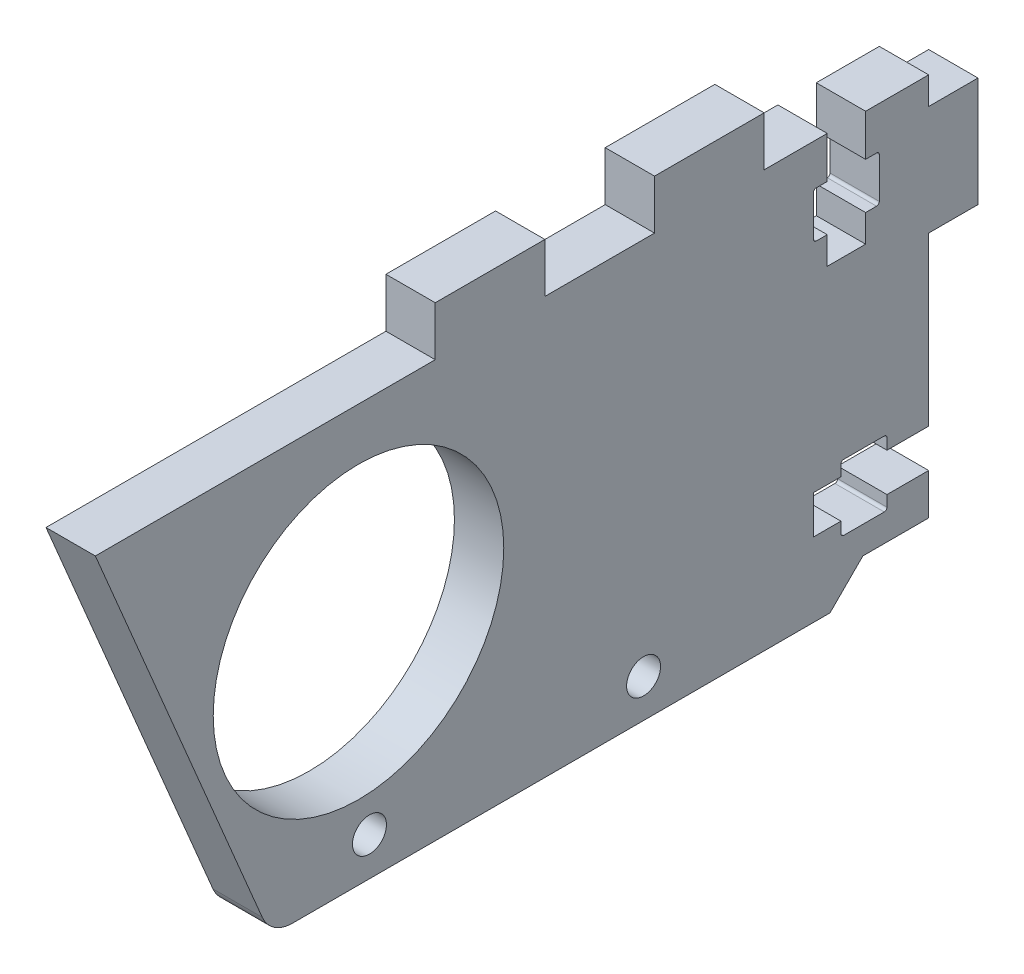
SolidWorks part; units mm, degrees
ref_plane "Front Plane" through (0, 0, 0) normal (0, 0, 1) x (1, 0, 0)
ref_plane "Top Plane" through (0, 0, 0) normal (0, 1, 0) x (1, 0, 0)
ref_plane "Right Plane" through (0, 0, 0) normal (1, 0, 0) x (0, 0, -1)
sketch "Sketch1" plane through (0, 0, 0) normal (1, 0, 0) x (0, 0, -1)
  line L0 (0, 0) -> (0, -35)
  line L1 (0, -35) -> (-76, 0)
  line L2 (-76, 0) -> (0, 0)
  dimension "D1" = 35
  dimension "D2" = 76
extrude "Boss-Extrude1" add sketch "Sketch1" along normal blind 4.5
sketch "Sketch2" plane through (4.5, 0, 0) normal (1, 0, 0) x (0, 0, -1)
  line L0 (0, -35) -> (0, 0) construction
  line L1 (-4.5, -2.5) -> (4.5, -2.5)
  line L2 (-4.5, -2.5) -> (-4.5, -12.5)
  line L3 (-4.5, -12.5) -> (4.5, -12.5)
  line L4 (4.5, -2.5) -> (4.5, -12.5)
  line L5 (-4.5, -2.5) -> (4.5, -12.5) construction
  line L6 (-4.5, -12.5) -> (4.5, -2.5) construction
  line L7 (0, 0) -> (-76, 0) construction
  point P0 (0, -7.5)
  dimension "D1" = 10
  dimension "D2" = 7.5
  dimension "D3" = 4.5
extrude "Boss-Extrude2" add sketch "Sketch2" against normal through all
sketch "Sketch3" plane through (4.5, 0, 0) normal (1, 0, 0) x (0, 0, -1)
  line L0 (0, -35) -> (-40, -35)
  line L1 (0, -25) -> (-76, 0)
  line L4 (0, -35) -> (0, -12.5) construction
  line L5 (0, -25) -> (0, -35)
  line L6 (-76, 0) -> (-40, -35)
  dimension "D1" = 40
  dimension "D2" = 10
extrude "Boss-Extrude3" add sketch "Sketch3" against normal through all
sketch "Sketch4" plane through (4.5, 0, 0) normal (1, 0, 0) x (0, 0, -1)
  line L0 (0, -29.5) -> (-10.5, -29.5) construction
  line L1 (0, -35) -> (0, -12.5) construction
  line L2 (0, -27.75) -> (-10.5, -27.75) construction
  line L3 (-10.5, -27.75) -> (-10.5, -31.25) construction
  line L4 (0, -31.25) -> (0, -27.75)
  line L5 (0, -27.75) -> (-3.8, -27.75)
  line L6 (-3.8, -27.75) -> (-3.8, -26.75)
  line L7 (-4.05, -26.5) -> (-7.75, -26.5)
  line L8 (-8, -26.75) -> (-8, -27.75)
  line L9 (-8, -27.75) -> (-10.5, -27.75)
  line L10 (-10.5, -27.75) -> (-10.5, -31.25)
  line L12 (0, -31.25) -> (-10.5, -31.25) construction
  line L13 (-8, -31.25) -> (-10.5, -31.25)
  line L14 (-8, -32.25) -> (-8, -31.25)
  line L15 (-4.05, -32.5) -> (-7.75, -32.5)
  line L16 (-3.8, -31.25) -> (-3.8, -32.25)
  line L17 (0, -31.25) -> (-3.8, -31.25)
  line L18 (4.5, -12.5) -> (4.5, -2.5) construction
  line L19 (0, -18.5) -> (-56.9714, -18.5) construction
  line L20 (-76, 0) -> (-40, -35) construction
  line L37 (0, -31.25) -> (-10.5, -31.25) construction
  arc A0 (-8, -32.25) -> (-7.75, -32.5) centre (-7.75, -32.25) ccw
  arc A1 (-4.05, -32.5) -> (-3.8, -32.25) centre (-4.05, -32.25) ccw
  arc A2 (-3.8, -26.75) -> (-4.05, -26.5) centre (-4.05, -26.75) ccw
  arc A3 (-7.75, -26.5) -> (-8, -26.75) centre (-7.75, -26.75) ccw
  point P10 (4.5, -7.5)
  point P20 (-8, -32.5)
  point P23 (-3.8, -32.5)
  point P26 (-3.8, -26.5)
  point P29 (-8, -26.5)
  dimension "D7" = 0.25
  dimension "D1" = 10.5
  dimension "D2" = 1.75
  dimension "D3" = 3
  dimension "D4" = 4.2
  dimension "D5" = 8
  dimension "D6" = 22
extrude "Cut-Extrude1" cut sketch "Sketch4" against normal through all
sketch "Sketch5" plane through (4.5, 0, 0) normal (1, 0, 0) x (0, 0, -1)
  line L0 (0, 0) -> (-76, 0) construction
  line L1 (-25, 4.5) -> (-15, 4.5)
  line L2 (-25, 4.5) -> (-25, 0)
  line L3 (0, 0) -> (-76, 0) construction
  line L4 (-15, 4.5) -> (-15, 0)
  line L5 (-25, 4.5) -> (-20, 0) construction
  line L6 (-20, 0) -> (-15, 4.5) construction
  line L7 (-30, 0) -> (-30, 4.5) construction
  line L8 (-40, 0) -> (-45, 4.5) construction
  line L9 (-35, 4.5) -> (-40, 0) construction
  line L10 (-45, 4.5) -> (-45, 0)
  line L12 (-35, 4.5) -> (-35, 0)
  line L13 (-35, 4.5) -> (-45, 4.5)
  line L14 (-20, 0) -> (-15, 4.5) construction
  line L15 (-15, 0) -> (-25, 0)
  line L16 (-35, 0) -> (-45, 0)
  point P0 (-20, 0)
  point P14 (-40, 0)
  dimension "D3" = 4.5
  dimension "D1" = 20
  dimension "D2" = 10
  dimension "D4" = 20
  dimension "D5" = 5
extrude "Boss-Extrude4" add sketch "Sketch5" against normal through all
sketch "Sketch8" [suppressed] plane through (4.5, 0, 0) normal (1, 0, 0) x (0, 0, -1)
  line L0 (-15, -30) -> (-27, -30) construction
  line L1 (-15, -35) -> (-27, -35)
  line L2 (-15, -25) -> (-27, -25)
  line L3 (-15, -35) -> (0, -35) construction
  line L4 (-15, -25) -> (-15, -35)
  arc A1 (-27, -25) -> (-27, -35) centre (-27, -30) ccw
  dimension "D5" = 5
  dimension "D1" = 0
  dimension "D2" = 12
  dimension "D3" = 0
  dimension "D4" = 10
extrude "Boss-Extrude5" [suppressed] add sketch "Sketch8" against normal up to surface (4.5 mm away)
sketch "Sketch9" [suppressed] plane through (4.5, 0, 0) normal (1, 0, 0) x (0, 0, -1)
  line L0 (-27, -30) -> (-22, -30) construction
  line L1 (-27, -27) -> (-22, -27)
  line L2 (-27, -33) -> (-22, -33)
  arc A0 (-27, -27) -> (-27, -33) centre (-27, -30) ccw
  arc A1 (-22, -33) -> (-22, -27) centre (-22, -30) ccw
  point P3 (-24.5, -30)
  dimension "D1" = 3
  dimension "D2" = 5
extrude "Cut-Extrude3" [suppressed] cut sketch "Sketch9" against normal through all
sketch "Sketch10" plane through (0, 0, 0) normal (-1, 0, 0) x (0, 0, 1)
  line L0 (40, -35) -> (76, -12)
  line L1 (76, -12) -> (76, 0)
  line L3 (76, 0) -> (40, -35)
  dimension "D1" = 12
extrude "Boss-Extrude6" [suppressed] add sketch "Sketch10" against normal through all
sketch "Sketch6" plane through (4.5, 0, 0) normal (1, 0, 0) x (0, 0, -1)
  line L0 (-30, 0) -> (-30, -10.5) construction
  line L1 (-25, 0) -> (-35, 0) construction
  line L2 (-28.25, -10.5) -> (-31.75, -10.5) construction
  line L3 (-31.75, -10.5) -> (-31.75, 0) construction
  line L4 (-28.25, 0) -> (-31.75, 0)
  line L5 (-31.75, 0) -> (-31.75, -3.8)
  line L6 (-31.75, -3.8) -> (-32.75, -3.8)
  line L7 (-33, -4.05) -> (-33, -7.75)
  line L8 (-32.75, -8) -> (-31.75, -8)
  line L9 (-31.75, -8) -> (-31.75, -10.5)
  line L10 (-31.75, -10.5) -> (-28.25, -10.5)
  line L11 (-28.25, -10.5) -> (-28.25, 0) construction
  line L12 (-28.25, -8) -> (-28.25, -10.5)
  line L13 (-27.25, -8) -> (-28.25, -8)
  line L14 (-27, -4.05) -> (-27, -7.75)
  line L15 (-28.25, -3.8) -> (-27.25, -3.8)
  line L16 (-28.25, 0) -> (-28.25, -3.8)
  arc A0 (-33, -7.75) -> (-32.75, -8) centre (-32.75, -7.75) ccw
  arc A1 (-32.75, -3.8) -> (-33, -4.05) centre (-32.75, -4.05) ccw
  arc A2 (-27.25, -3.8) -> (-27, -4.05) centre (-27.25, -4.05) cw
  arc A3 (-27, -7.75) -> (-27.25, -8) centre (-27.25, -7.75) cw
  point P12 (-33, -8)
  point P15 (-33, -3.8)
  point P26 (-27, -3.8)
  point P27 (-27, -8)
  dimension "D1" = 10.5
  dimension "D2" = 1.75
  dimension "D4" = 4.2
  dimension "D6" = 0.25
  dimension "D3" = 8
  dimension "D5" = 3
extrude "Cut-Extrude2" [suppressed] cut sketch "Sketch6" against normal through all
sketch "Sketch11" plane through (0, 0, 0) normal (-1, 0, 0) x (0, 0, 1)
  line L0 (7.5, 0) -> (7.5, -10.5) construction
  line L1 (0, 0) -> (15, 0) construction
  line L2 (5.75, -10.5) -> (9.25, -10.5)
  line L3 (9.25, -10.5) -> (9.25, -8)
  line L4 (9.25, -8) -> (10.25, -8)
  line L5 (10.5, -7.75) -> (10.5, -4.05)
  line L6 (10.25, -3.8) -> (9.25, -3.8)
  line L7 (9.25, -3.8) -> (9.25, 0)
  line L8 (9.25, 0) -> (5.75, 0)
  line L9 (9.25, -8) -> (9.25, -3.8) construction
  line L10 (0, 0) -> (15, 0) construction
  line L11 (5.75, -8) -> (5.75, -3.8) construction
  line L12 (5.75, -3.8) -> (5.75, 0)
  line L13 (4.75, -3.8) -> (5.75, -3.8)
  line L14 (4.5, -7.75) -> (4.5, -4.05)
  line L15 (5.75, -8) -> (4.75, -8)
  line L16 (5.75, -10.5) -> (5.75, -8)
  arc A0 (10.5, -4.05) -> (10.25, -3.8) centre (10.25, -4.05) ccw
  arc A1 (4.75, -3.8) -> (4.5, -4.05) centre (4.75, -4.05) ccw
  arc A2 (10.25, -8) -> (10.5, -7.75) centre (10.25, -7.75) ccw
  arc A3 (4.5, -7.75) -> (4.75, -8) centre (4.75, -7.75) ccw
  point P11 (7.5, 0)
  point P22 (10.5, -3.8)
  point P25 (4.5, -3.8)
  point P28 (10.5, -8)
  point P31 (4.5, -8)
  dimension "D7" = 0.25
  dimension "D1" = 10.5
  dimension "D3" = 3
  dimension "D8" = 0.25
  dimension "D2" = 4.2
  dimension "D4" = 8
  dimension "D5" = 1.75
  dimension "D6" = 0
extrude "Cut-Extrude4" cut sketch "Sketch11" against normal through all
sketch "Sketch12" plane through (0, 0, 0) normal (-1, 0, 0) x (0, 0, 1)
  line L0 (52, -18) -> (40, -6) construction
  line L1 (52, -18) -> (52, -4.75) construction
  line L2 (52, -18) -> (64, -6) construction
  line L3 (52, -18) -> (38.75, -18) construction
  line L4 (52, -18) -> (40, -30) construction
  line L5 (52, -18) -> (40, -6) construction
  line L6 (0, -27.75) -> (0, -12.5) construction
  line L7 (25, 0) -> (35, 0) construction
  circle A0 centre (52, -18) radius 13.25
  circle A1 centre (40, -6) radius 1.55
  circle A2 centre (64, -6) radius 1.55
  circle A3 centre (40, -30) radius 1.55
  dimension "D1" = 26.5
  dimension "D2" = 3.1
  dimension "D3" = 12
  dimension "D4" = 45
  dimension "D5" = 52
  dimension "D6" = 18
extrude "Cut-Extrude5" [suppressed] cut sketch "Sketch12" against normal through all
sketch "Sketch13" [suppressed] plane through (0, 0, 0) normal (-1, 0, 0) x (0, 0, 1)
  line L0 (42.339, -13.1717) -> (46.9952, -11.3497)
  line L1 (36.718, -29.4206) -> (39.2531, -33.7303)
  line L6 (30, -18) -> (76, 0) construction
  line L7 (30, -18) -> (40, -35) construction
  arc A0 (36.718, -29.4206) -> (42.339, -13.1717) centre (30, -18) ccw
  arc A1 (39.2531, -33.7303) -> (46.9952, -11.3497) centre (30, -18) ccw
  circle A3 centre (30, -18) radius 13.25 construction
  dimension "D1" = 5
extrude "Boss-Extrude7" [suppressed] add sketch "Sketch13" against normal through all
sketch "Sketch14" [suppressed] plane through (0, 0, 0) normal (-1, 0, 0) x (0, 0, 1)
  line L0 (30, -4.75) -> (30, -31.25) construction
  line L1 (30, -18) -> (42, -30) construction
  circle A1 centre (42, -30) radius 3.5
  arc A3 (42.339, -13.1717) -> (36.718, -29.4206) centre (30, -18) ccw construction
  dimension "D2" = 7
  dimension "D1" = 45
  dimension "D3" = 12
extrude "Boss-Extrude8" [suppressed] add sketch "Sketch14" against normal through all
sketch "Sketch15" [suppressed] plane through (0, 0, 0) normal (-1, 0, 0) x (0, 0, 1)
  line L0 (44.4749, -32.4749) -> (30, -18) construction
  circle A1 centre (42, -30) radius 1.55
  arc A2 (40.305, -33.0622) -> (45.0622, -28.305) centre (42, -30) ccw construction
  arc A4 (40.305, -33.0622) -> (45.0622, -28.305) centre (42, -30) ccw construction
  dimension "D1" = 3.1
extrude "Cut-Extrude6" [suppressed] cut sketch "Sketch15" against normal through all
sketch "Sketch16" plane through (4.5, 0, 0) normal (1, 0, 0) x (0, 0, -1)
  line L0 (0, -34.5) -> (-39, -34.5) construction
  line L1 (0, -27.75) -> (0, -12.5) construction
  line L2 (-15, -34.5) -> (-39, -34.5) construction
  line L3 (-15, -38.5) -> (-39, -38.5)
  line L4 (-15, -30.5) -> (-39, -30.5)
  arc A0 (-15, -38.5) -> (-15, -30.5) centre (-15, -34.5) ccw
  arc A1 (-39, -30.5) -> (-39, -38.5) centre (-39, -34.5) ccw
  point P5 (-27, -34.5)
  point P12 (0, -20.125)
  dimension "D1" = 4
  dimension "D2" = 34.5
  dimension "D3" = 39
  dimension "D4" = 15
extrude "Boss-Extrude9" [suppressed] add sketch "Sketch16" against normal through all
sketch "Sketch17" [suppressed] plane through (4.5, 0, 0) normal (1, 0, 0) x (0, 0, -1)
  line L0 (-43, -34.5) -> (0, -34.5) construction
  line L1 (0, -27.75) -> (0, -12.5) construction
  line L2 (-26.5, -34.5) -> (-26.5, -20.0064) construction
  arc A0 (-42.1823, -32.0766) -> (-39, -38.5) centre (-39, -34.5) ccw construction
  circle A1 centre (-39, -34.5) radius 1.55
  circle A2 centre (-14, -34.5) radius 1.55
  dimension "D1" = 3.1
  dimension "D2" = 12.5
extrude "Cut-Extrude7" [suppressed] cut sketch "Sketch17" against normal through all
sketch "Sketch18" [suppressed] plane through (4.5, 0, 0) normal (1, 0, 0) x (0, 0, -1)
  line L0 (-15, -38.5) -> (0, -35)
  line L1 (0, -35) -> (-11.0314, -35)
  line L2 (-11.0314, -35) -> (-15, -38.5)
extrude "Boss-Extrude10" [suppressed] add sketch "Sketch18" against normal through all
sketch "Sketch20" plane through (4.5, 0, 0) normal (1, 0, 0) x (0, 0, -1)
  line L0 (0, -35) -> (0, -31.25) construction
  line L1 (-9, -38) -> (-58.0081, -38)
  line L2 (-60.773, -36.1642) -> (-76, 0)
  line L3 (-76, 0) -> (-40, -35)
  line L4 (-40, -35) -> (-6, -35)
  line L5 (-9, -38) -> (-6, -35)
  line L6 (-60.773, -36.1642) -> (-60, -38) construction
  line L7 (-60, -38) -> (-58.0081, -38) construction
  arc A1 (-58.0081, -38) -> (-60.773, -36.1642) centre (-58.0081, -35) cw
  point P0 (0, -33.125)
  point P14 (-60, -38)
  dimension "D3" = 6
  dimension "D4" = 3
  dimension "D1" = 60
  dimension "D2" = 3
  dimension "D5" = 135
extrude "Boss-Extrude11" add sketch "Sketch20" against normal through all
sketch "Sketch21" plane through (4.5, 0, 0) normal (1, 0, 0) x (0, 0, -1)
  line L0 (0, -34.5) -> (-61.4737, -34.5) construction
  line L1 (0, -35) -> (0, -31.25) construction
  line L2 (-76, 0) -> (-60.773, -36.1642) construction
  line L3 (0, -27.75) -> (0, -12.5) construction
  circle A0 centre (-51, -34.5) radius 1.55
  circle A1 centre (-26, -34.5) radius 1.55
  dimension "D2" = 3.1
  dimension "D3" = 3.1
  dimension "D1" = 25
  dimension "D4" = 34.5
  dimension "D5" = 26
extrude "Cut-Extrude8" cut sketch "Sketch21" against normal through all
sketch "Sketch22" plane through (4.5, 0, 0) normal (1, 0, 0) x (0, 0, -1)
  line L0 (0, -27.75) -> (0, -12.5) construction
  line L1 (-25, 0) -> (-35, 0) construction
  circle A0 centre (-52, -18) radius 13.25
  dimension "D3" = 26.5
  dimension "D1" = 52
  dimension "D2" = 18
extrude "Cut-Extrude9" cut sketch "Sketch22" against normal through all
equation "\"X-ROD-SPACING\"=45"
equation "\"Y-ROD-SPACING\"=75"
equation "\"Z-ROD-SPACING\"=17.5"
equation "\"Y-BED-OFFSET\"=2"
equation "\"Y-BED-ROD-INSET\"=3.5"
equation "\"Y-BED-SCREW-SPACING\"=209"
equation "\"Y-BED-SCREW-CUTOUT-SLOT-HEIGHT\"=2"
equation "\"T-SLOT-NUT-FILLET-RADIUS\"=0.25"
equation "\"T-SLOT-SCREW-SHAFT-RADIUS\"=1.75"
equation "\"T-SLOT-SCREW-SHAFT-CUTOUT-LENGTH\"=10.5"
equation "\"T-SLOT-NUT-DEPTH\"=4.2"
equation "\"T-SLOT-NUT-WIDTH\"=3"
equation "\"T-SLOT-NUT-END-DISTANCE\"=8"
equation "\"ACRYLIC-THICKNESS\"=10"
equation "\"ACRYLIC-THICKNESS2\"=4.5"
equation "\"ACRYLIC-TAB-CUTOUT-SIZE\"=\"ACRYLIC-THICKNESS\"+\"ACRYLIC-TAB-TOLERANCE\"*2"
equation "\"ACRYLIC-TAB-WIDTH\"=\"ACRYLIC-THICKNESS\""
equation "\"ACRYLIC-M3-HOLE\"=3.1"
equation "\"SMOOTHROD-CAP-SCREW-DISTANCE\"=20"
equation "\"FRAME-WIDTH-INNER\"=370"
equation "\"NEMA17-HOLE-SPACING\"=31"
equation "\"NEMA17-CENTRAL-CUTOUT\"=22.5"
equation "\"Z-BRACKET-REACH\"=55"
equation "\"Z-ROD-INSET\"=16"
equation "\"TOP-BRACKET-SPACING\"=40"
equation "\"SMOOTHROD-X-LENGTH\"=350"
equation "\"SMOOTHROD-Y-LENGTH\"=350"
equation "\"SMOOTHROD-Z-LENGTH\"=350"
equation "\"SMOOTHROD-TIGHTENING-HEADROOM\"=.25"
equation "\"LEADSCREW-Z-LENGTH\"=300"
equation "\"SCREW-LENGTH-FRAME\"=\"ACRYLIC-THICKNESS\" + 10"
equation "\"SCREW-LENGTH-MOTOR\"=\"ACRYLIC-THICKNESS\" + 5"
equation "\"SCREW-LENGTH-EXTRUDER\"=28"
equation "\"SCREW-HEAD-RADIUS\"=6"
equation "\"PRINTED-X-SMOOTHROD-DIAMETER\"=8.2"
equation "\"PRINTED-X-SMOOTHROD-CUTOUT\"=10"
equation "\"PRINTED-X-BASE-HEIGHT\"=10"
equation "\"PRINTED-LM8UU-CUTOUT-SIZE\"=15.25"
equation "\"PRINTED-LM8UU-CUTOUT-LENGTH\"=24.5"
equation "\"PRINTED-X-IDLER-HEIGHT\"=16"
equation "\"PSU-MOUNTING-WIDTH\"=95"
equation "\"PSU-MOUNTING-HEIGHT\"=177"
equation "\"Y-BELT-TO-ROD-DISTANCE\"=20"
equation "\"SPOOL-HOLDER-ROD-SPACING\"=150"
equation "\"ACRYLIC-X-CARRIAGE-WIDTH\"=55"
equation "\"ACRYLIC-X-CARRIAGE-HEIGHT\"=75"
equation "\"ACRYLIC-X-CARRIAGE-SCREW-SPACING-X\"=15"
equation "\"ACRYLIC-X-CARRIAGE-SCREW-SPACING-Y\"=33"
equation "\"ACRYLIC-X-CARRIAGE-CENTER-TAB-SPACING\"=14"
equation "\"ACRYLIC-X-CARRIAGE-EXTRUDER-SHELF-DEPTH\"=\"ACRYLIC-X-CARRIAGE-EXTRUDER-OFFSET\" + 28"
equation "\"D2@Sketch1\"=\"ACRYLIC-X-CARRIAGE-DUAL-MOUNT-PLATE-DEPTH\""
equation "\"D1@Boss-Extrude1\"=\"ACRYLIC-THICKNESS2\""
equation "\"D1@Sketch2\"=\"ACRYLIC-TAB-WIDTH\""
equation "\"D3@Sketch2\"=\"ACRYLIC-THICKNESS2\""
equation "\"ACRYLIC-X-CARRIAGE-LM8UU-CUTOUT-WIDTH\"=24.25"
equation "\"ACRYLIC-X-CARRIAGE-EXTRUDER-BRACE-SPACING\"=23"
equation "\"ACRYLIC-X-CARRIAGE-EXTRUDER-BRACE-HEIGHT\"=35"
equation "\"D1@Sketch1\"=\"ACRYLIC-X-CARRIAGE-EXTRUDER-BRACE-HEIGHT\""
equation "\"D1@Sketch4\"=\"T-SLOT-SCREW-SHAFT-CUTOUT-LENGTH\""
equation "\"D2@Sketch4\"=\"T-SLOT-SCREW-SHAFT-RADIUS\""
equation "\"D3@Sketch4\"=\"T-SLOT-NUT-WIDTH\""
equation "\"D4@Sketch4\"=\"T-SLOT-NUT-DEPTH\""
equation "\"D5@Sketch4\"=\"T-SLOT-NUT-END-DISTANCE\""
equation "\"D7@Sketch4\"=\"T-SLOT-NUT-FILLET-RADIUS\""
equation "\"ACRYLIC-X-CARRIAGE-EXTRUDER-BRACE-SCREW-SPACING\"=22"
equation "\"D6@Sketch4\"=\"ACRYLIC-X-CARRIAGE-EXTRUDER-BRACE-SCREW-SPACING\""
equation "\"ACRYLIC-X-CARRIAGE-EXTRUDER-BRACE-TAB-OFFSET\"=20"
equation "\"D1@Sketch5\"=\"ACRYLIC-X-CARRIAGE-EXTRUDER-BRACE-TAB-OFFSET\""
equation "\"D2@Sketch5\"=\"ACRYLIC-TAB-WIDTH\""
equation "\"D3@Sketch5\"=\"ACRYLIC-THICKNESS2\""
equation "\"ACRYLIC-X-CARRIAGE-EXTRUDER-OFFSET\"=26"
equation "\"ACRYLIC-X-CARRIAGE-EXTRUDER-ANGLE\"=90"
equation "\"D1@Sketch6\"=\"T-SLOT-SCREW-SHAFT-CUTOUT-LENGTH\""
equation "\"D2@Sketch6\"=\"T-SLOT-SCREW-SHAFT-RADIUS\""
equation "\"D3@Sketch6\"=\"T-SLOT-NUT-END-DISTANCE\""
equation "\"D4@Sketch6\"=\"T-SLOT-NUT-DEPTH\""
equation "\"D5@Sketch6\"=\"T-SLOT-NUT-WIDTH\""
equation "\"D6@Sketch6\"=\"T-SLOT-NUT-FILLET-RADIUS\""
equation "\"D1@Sketch11\"=\"T-SLOT-SCREW-SHAFT-CUTOUT-LENGTH\""
equation "\"D2@Sketch11\"=\"T-SLOT-NUT-DEPTH\""
equation "\"D3@Sketch11\"=\"T-SLOT-NUT-WIDTH\""
equation "\"D4@Sketch11\"=\"T-SLOT-NUT-END-DISTANCE\""
equation "\"D5@Sketch11\"=\"T-SLOT-SCREW-SHAFT-RADIUS\""
equation "\"D7@Sketch11\"=\"T-SLOT-NUT-FILLET-RADIUS\""
equation "\"D8@Sketch11\"=\"T-SLOT-NUT-FILLET-RADIUS\""
equation "\"D2@Sketch12\"=\"ACRYLIC-M3-HOLE\""
equation "\"D1@Sketch15\"=\"ACRYLIC-M3-HOLE\""
equation "\"D1@Sketch17\"=\"ACRYLIC-M3-HOLE\""
equation "\"D2@Sketch21\"=\"ACRYLIC-M3-HOLE\""
equation "\"D3@Sketch21\"=\"ACRYLIC-M3-HOLE\""
equation "\"ACRYLIC-TAB-TOLERANCE\"=.1"
equation "\"PRINTED-M3-HOLE\"=3.5"
equation "\"PRINTED-M3-NUT-AF\"=6.25"
equation "\"ACRYLIC-X-CARRIAGE-LM8UU-CUTOUT-HEIGHT\"=11.5"
equation "\"ACRYLIC-X-CARRIAGE-DUAL-WIDTH-MULTIPLIER\"=1.65"
equation "\"ACRYLIC-X-CARRIAGE-DUAL-HOTEND-SPACING\"=42"
equation "\"ACRYLIC-X-CARRIAGE-DUAL-WIDTH\"=103"
equation "\"ACRYLIC-X-CARRIAGE-DUAL-HOTEND-SEPARATION\"=35"
equation "\"ACRYLIC-X-CARRIAGE-DUAL-MOUNT-PLATE-DEPTH\"=76"
equation "\"ACRYLIC-X-CARRIAGE-DUAL-MOUNT-BRACE-WIDTH\"=45"
equation "\"ACRYLIC-X-CARRIAGE-DUAL-MOUNT-SCREW-WIDTH\"=40"
equation "\"BLOWER-FAN-WIDTH\"=15"
equation "\"ACRYLIC-X-CARRIAGE-DUAL-FAN-OFFSET\"=52"
equation "\"D5@Sketch12\"=\"ACRYLIC-X-CARRIAGE-DUAL-FAN-OFFSET\""
equation "\"D1@Sketch22\"=\"ACRYLIC-X-CARRIAGE-DUAL-FAN-OFFSET\""
